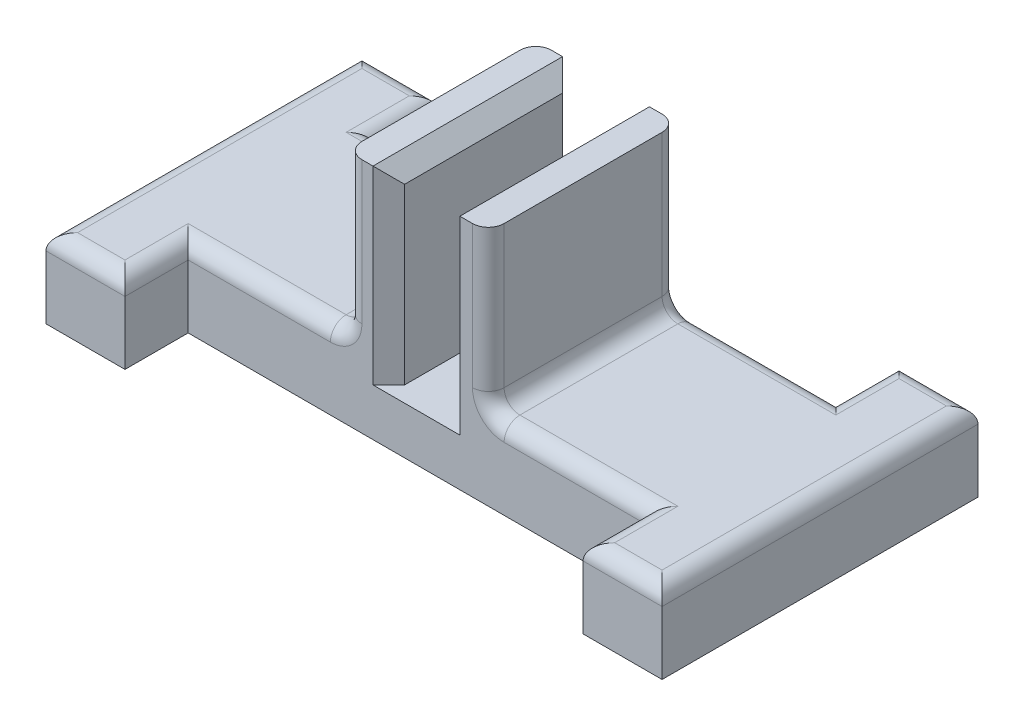
SolidWorks part; units mm, degrees
ref_plane "Front Plane" through (0, 0, 0) normal (0, 0, 1) x (1, 0, 0)
ref_plane "Top Plane" through (0, 0, 0) normal (0, 1, 0) x (1, 0, 0)
ref_plane "Right Plane" through (0, 0, 0) normal (1, 0, 0) x (0, 0, -1)
sketch "Sketch1" plane through (0, 0, 0) normal (0, 0, 1) x (1, 0, 0)
  line L1 (-4.5, 7.5) -> (4.5, 7.5)
  line L2 (-4.5, 7.5) -> (-4.5, -7.5)
  line L3 (-4.5, -7.5) -> (4.5, -7.5)
  line L4 (4.5, 7.5) -> (4.5, -7.5)
  line L5 (-4.5, 7.5) -> (4.5, -7.5) construction
  line L6 (-4.5, -7.5) -> (4.5, 7.5) construction
  line L7 (4.5, -2.5) -> (19.5, -2.5)
  line L8 (4.5, -2.5) -> (4.5, -7.5)
  line L9 (4.5, -7.5) -> (19.5, -7.5)
  line L10 (19.5, -2.5) -> (19.5, -7.5)
  line L11 (-4.5, -7.5) -> (-19.5, -7.5)
  line L12 (-4.5, -7.5) -> (-4.5, -2.5)
  line L13 (-4.5, -2.5) -> (-19.5, -2.5)
  line L14 (-19.5, -7.5) -> (-19.5, -2.5)
  point P0 (0, 0)
  dimension "D1" = 15
  dimension "D2" = 9
  dimension "D3" = 15
  dimension "D4" = 5
  dimension "D5" = 5
  dimension "D6" = 15
extrude "Boss-Extrude1" add sketch "Sketch1" along normal blind 12 contours L4 L1 L2 L3 | L14 L11 L2 L13 | L10 L7 L4 L9
sketch "Sketch2" plane through (0, 7.5, 0) normal (0, 1, 0) x (1, 0, 0)
  line L0 (-4.5, 0) -> (4.5, 0) construction
  line L1 (-1.8, 0) -> (1.7, 0)
  line L2 (-1.8, 0) -> (-1.8, -12)
  line L3 (-1.8, -12) -> (1.7, -12)
  line L4 (1.7, 0) -> (1.7, -12)
  line L5 (-4.5, -12) -> (4.5, -12) construction
  line L6 (-4.5, -12) -> (-4.5, 0) construction
  dimension "D1" = 3.5
  dimension "D2" = 2.7
extrude "Cut-Extrude1" cut sketch "Sketch2" against normal blind 12
sketch "Sketch3" plane through (-19.5, 0, 0) normal (-1, 0, 0) x (0, 0, 1)
  line L0 (0, -7.5) -> (0, -2.5) construction
  line L1 (-4, -2.5) -> (16, -2.5)
  line L2 (-4, -2.5) -> (-4, -7.5)
  line L3 (-4, -7.5) -> (16, -7.5)
  line L4 (16, -2.5) -> (16, -7.5)
  dimension "D1" = 20
  dimension "D2" = 4
extrude "Boss-Extrude2" add sketch "Sketch3" against normal blind 5
sketch "Sketch4" plane through (19.5, 0, 0) normal (1, 0, 0) x (0, 0, -1)
  line L1 (-16, -2.5) -> (4, -2.5)
  line L2 (-16, -2.5) -> (-16, -7.5)
  line L3 (-16, -7.5) -> (4, -7.5)
  line L4 (4, -2.5) -> (4, -7.5)
extrude "Boss-Extrude3" add sketch "Sketch4" against normal blind 5
chamfer "Chamfer1" distance 1 angle 45 6 edges at (1.7, 1.5, 0) (1.7, 1.5, 12) (1.7, 7.5, 6) (-1.8, 1.5, 12) (-1.8, 1.5, 0) (-1.8, 7.5, 6)
fillet "Fillet1" radius 1 20 edges at (4.5, 2.5, 0) (4.5, 2.5, 12) (-4.5, 2.5, 0) (-4.5, 2.5, 12) (17, -2.5, 16) (14.5, -2.5, 14) (9.5, -2.5, 0) (9.5, -2.5, 12) (4.5, -2.5, 6) (14.5, -2.5, -2) (17, -2.5, -4) (19.5, -2.5, 6) (-17, -2.5, -4) (-14.5, -2.5, -2) (-9.5, -2.5, 12) (-9.5, -2.5, 0) (-4.5, -2.5, 6) (-14.5, -2.5, 14) (-17, -2.5, 16) (-19.5, -2.5, 6)
